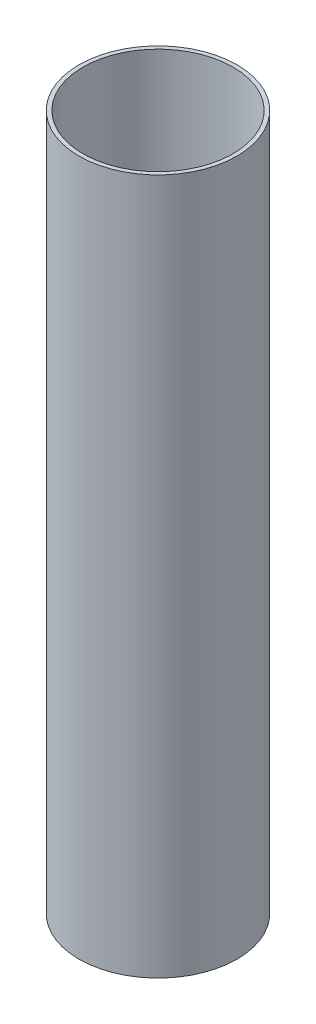
SolidWorks part; units mm, degrees
material "6061-T6 (SS)"
ref_plane "Front Plane" through (0, 0, 0) normal (0, 0, 1) x (1, 0, 0)
ref_plane "Top Plane" through (0, 0, 0) normal (0, 1, 0) x (1, 0, 0)
ref_plane "Right Plane" through (0, 0, 0) normal (1, 0, 0) x (0, 0, -1)
sketch "Sketch1" plane through (0, 0, 0) normal (0, 0, 1) x (1, 0, 0)
  line L0 (0, 0) -> (0, 619.3135) construction
  line L2 (60.325, 0) -> (63.5, 0)
  line L3 (60.325, 0) -> (60.325, 558.8)
  line L4 (60.325, 558.8) -> (63.5, 558.8)
  line L5 (63.5, 0) -> (63.5, 558.8)
  point P7 (0, 292.5993)
  point P8 (63.5, 268.0312)
  point P9 (0, 619.3135)
  dimension "D1" = 127
  dimension "D2" = 3.175
  dimension "D3" = 558.8
revolve "Revolve1" add sketch "Sketch1" angle 360 about L0
